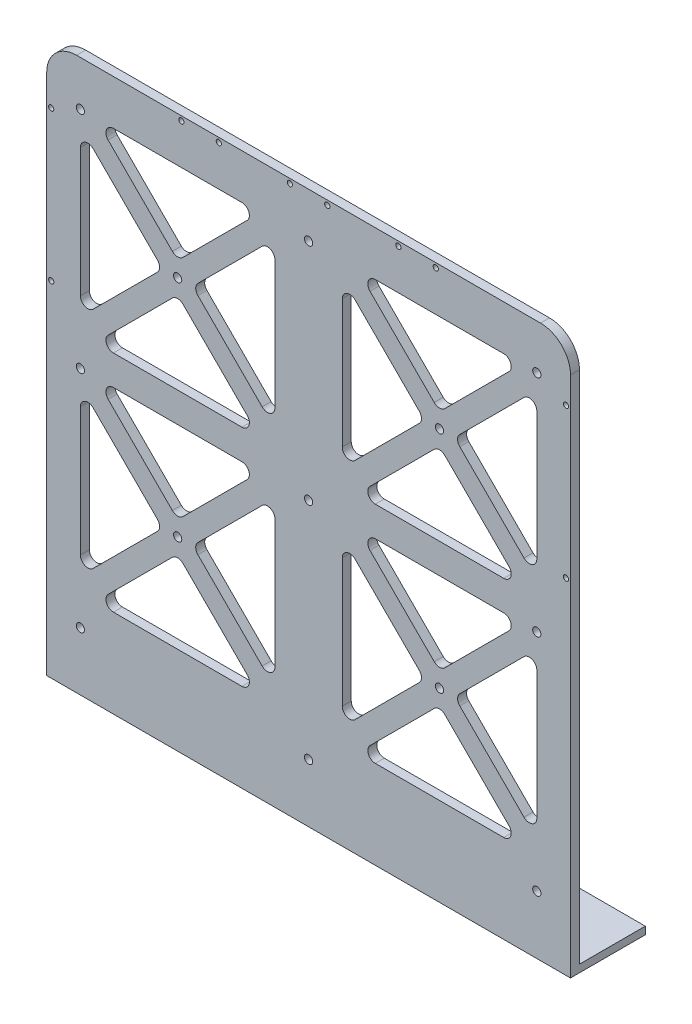
SolidWorks part; units mm, degrees
material "6061 合金"
ref_plane "前视基准面" through (0, 0, 0) normal (0, 0, 1) x (1, 0, 0)
ref_plane "上视基准面" through (0, 0, 0) normal (0, 1, 0) x (1, 0, 0)
ref_plane "右视基准面" through (0, 0, 0) normal (1, 0, 0) x (0, 0, -1)
other "Configuration Table"
sketch "草图1" plane through (0, 0, 0) normal (0, 1, 0) x (1, 0, 0)
  line L0 (0, 55.3951) -> (0, -55.5471) construction
  line L1 (-216.8213, 25) -> (288.5349, 25) construction
  line L2 (-175, 50) -> (175, 50)
  line L3 (-175, 50) -> (-175, 0)
  line L4 (-175, 0) -> (175, 0)
  line L5 (175, 50) -> (175, 0)
  circle A0 centre (130, 25) radius 2.75
  circle A1 centre (50, 25) radius 2.75
  circle A2 centre (-130, 25) radius 2.75
  circle A3 centre (-50, 25) radius 2.75
  dimension "D3" = 5.5
  dimension "D1" = 50
  dimension "D2" = 350
  dimension "D4" = 80
  dimension "D5" = 50
extrude "凸台-拉伸1" add sketch "草图1" along normal blind 5
sketch "草图2" plane through (0, 5, 0) normal (0, 1, 0) x (1, 0, 0)
  line L0 (-175, 50) -> (-175, 0) construction
  line L1 (-175, 6) -> (175, 6)
  line L2 (-175, 6) -> (-175, 0)
  line L3 (-175, 0) -> (175, 0)
  line L4 (175, 6) -> (175, 0)
  dimension "D1" = 6
extrude "凸台-拉伸2" add sketch "草图2" along normal blind 364
sketch "草图3" plane through (0, 0, -6) normal (0, 0, -1) x (-1, 0, 0)
  line L0 (83.9645, 137.5355) -> (41.0355, 180.4645)
  line L1 (0, 0) -> (0, 572.5398) construction
  line L2 (44.5711, 189) -> (130.4289, 189)
  line L15 (133.9645, 180.4645) -> (91.0355, 137.5355)
  line L28 (44.5711, 339) -> (130.4289, 339)
  line L29 (133.9645, 330.4645) -> (91.0355, 287.5355)
  line L30 (83.9645, 287.5355) -> (41.0355, 330.4645)
  line L31 (-175, 369) -> (175, 369) construction
  line L32 (87.5, 645.5729) -> (87.5, -148.8574) construction
  line L33 (73.9645, 120.4645) -> (31.0355, 77.5355)
  line L34 (175, 369) -> (175, 5) construction
  line L35 (101.0355, 277.5355) -> (143.9645, 320.4645)
  line L36 (152.5, 316.9289) -> (152.5, 231.0711)
  line L37 (143.9645, 227.5355) -> (101.0355, 270.4645)
  line L38 (91.0355, 260.4645) -> (133.9645, 217.5355)
  line L39 (130.4289, 209) -> (44.5711, 209)
  line L40 (41.0355, 217.5355) -> (83.9645, 260.4645)
  line L41 (73.9645, 270.4645) -> (31.0355, 227.5355)
  line L42 (22.5, 231.0711) -> (22.5, 316.9289)
  line L43 (31.0355, 320.4645) -> (73.9645, 277.5355)
  line L104 (22.5, 81.0711) -> (22.5, 166.9289)
  line L105 (31.0355, 170.4645) -> (73.9645, 127.5355)
  line L106 (101.0355, 127.5355) -> (143.9645, 170.4645)
  line L107 (152.5, 166.9289) -> (152.5, 81.0711)
  line L108 (143.9645, 77.5355) -> (101.0355, 120.4645)
  line L109 (91.0355, 110.4645) -> (133.9645, 67.5355)
  line L110 (130.4289, 59) -> (44.5711, 59)
  line L111 (41.0355, 67.5355) -> (83.9645, 110.4645)
  line L124 (-91.0355, 137.5355) -> (-133.9645, 180.4645)
  line L125 (-130.4289, 189) -> (-44.5711, 189)
  line L126 (-41.0355, 180.4645) -> (-83.9645, 137.5355)
  line L127 (-101.0355, 120.4645) -> (-143.9645, 77.5355)
  line L128 (-152.5, 81.0711) -> (-152.5, 166.9289)
  line L129 (-143.9645, 170.4645) -> (-101.0355, 127.5355)
  line L130 (-73.9645, 127.5355) -> (-31.0355, 170.4645)
  line L131 (-22.5, 166.9289) -> (-22.5, 81.0711)
  line L132 (-31.0355, 77.5355) -> (-73.9645, 120.4645)
  line L133 (-83.9645, 110.4645) -> (-41.0355, 67.5355)
  line L134 (-44.5711, 59) -> (-130.4289, 59)
  line L135 (-133.9645, 67.5355) -> (-91.0355, 110.4645)
  line L148 (-91.0355, 287.5355) -> (-133.9645, 330.4645)
  line L149 (-130.4289, 339) -> (-44.5711, 339)
  line L150 (-41.0355, 330.4645) -> (-83.9645, 287.5355)
  line L151 (-101.0355, 270.4645) -> (-143.9645, 227.5355)
  line L152 (-152.5, 231.0711) -> (-152.5, 316.9289)
  line L153 (-143.9645, 320.4645) -> (-101.0355, 277.5355)
  line L154 (-73.9645, 277.5355) -> (-31.0355, 320.4645)
  line L155 (-22.5, 316.9289) -> (-22.5, 231.0711)
  line L156 (-31.0355, 227.5355) -> (-73.9645, 270.4645)
  line L157 (-83.9645, 260.4645) -> (-41.0355, 217.5355)
  line L158 (-44.5711, 209) -> (-130.4289, 209)
  line L159 (-133.9645, 217.5355) -> (-91.0355, 260.4645)
  line L160 (83.9645, -12.4645) -> (41.0355, 30.4645) [skipped]
  line L161 (133.9645, 30.4645) -> (91.0355, -12.4645) [skipped]
  line L162 (73.9645, -29.5355) -> (31.0355, -72.4645) [skipped]
  line L163 (22.5, -68.9289) -> (22.5, 16.9289) [skipped]
  line L164 (31.0355, 20.4645) -> (73.9645, -22.4645) [skipped]
  line L165 (101.0355, -22.4645) -> (143.9645, 20.4645) [skipped]
  line L166 (152.5, 16.9289) -> (152.5, -68.9289) [skipped]
  line L167 (143.9645, -72.4645) -> (101.0355, -29.5355) [skipped]
  line L168 (91.0355, -39.5355) -> (133.9645, -82.4645) [skipped]
  line L169 (130.4289, -91) -> (44.5711, -91) [skipped]
  line L170 (41.0355, -82.4645) -> (83.9645, -39.5355) [skipped]
  line L171 (-91.0355, -12.4645) -> (-133.9645, 30.4645) [skipped]
  line L172 (-41.0355, 30.4645) -> (-83.9645, -12.4645) [skipped]
  line L173 (-101.0355, -29.5355) -> (-143.9645, -72.4645) [skipped]
  line L174 (-152.5, -68.9289) -> (-152.5, 16.9289) [skipped]
  line L175 (-143.9645, 20.4645) -> (-101.0355, -22.4645) [skipped]
  line L176 (-73.9645, -22.4645) -> (-31.0355, 20.4645) [skipped]
  line L177 (-22.5, 16.9289) -> (-22.5, -68.9289) [skipped]
  line L178 (-31.0355, -72.4645) -> (-73.9645, -29.5355) [skipped]
  line L179 (-83.9645, -39.5355) -> (-41.0355, -82.4645) [skipped]
  line L180 (-44.5711, -91) -> (-130.4289, -91) [skipped]
  line L181 (-133.9645, -82.4645) -> (-91.0355, -39.5355) [skipped]
  line L182 (44.5711, 39) -> (130.4289, 39) [skipped]
  line L183 (-130.4289, 39) -> (-44.5711, 39) [skipped]
  arc A0 (22.5, 316.9289) -> (31.0355, 320.4645) centre (27.5, 316.9289) cw
  arc A1 (31.0355, 227.5355) -> (22.5, 231.0711) centre (27.5, 231.0711) cw
  arc A2 (73.9645, 270.4645) -> (73.9645, 277.5355) centre (70.4289, 274) ccw
  arc A3 (44.5711, 209) -> (41.0355, 217.5355) centre (44.5711, 214) cw
  arc A4 (130.4289, 209) -> (133.9645, 217.5355) centre (130.4289, 214) ccw
  arc A5 (91.0355, 260.4645) -> (83.9645, 260.4645) centre (87.5, 256.9289) ccw
  arc A6 (101.0355, 270.4645) -> (101.0355, 277.5355) centre (104.5711, 274) cw
  arc A7 (143.9645, 227.5355) -> (152.5, 231.0711) centre (147.5, 231.0711) ccw
  arc A8 (152.5, 316.9289) -> (143.9645, 320.4645) centre (147.5, 316.9289) ccw
  arc A9 (91.0355, 287.5355) -> (83.9645, 287.5355) centre (87.5, 291.0711) cw
  arc A10 (133.9645, 330.4645) -> (130.4289, 339) centre (130.4289, 334) ccw
  arc A11 (41.0355, 330.4645) -> (44.5711, 339) centre (44.5711, 334) cw
  arc A12 (41.0355, 180.4645) -> (44.5711, 189) centre (44.5711, 184) cw
  arc A13 (91.0355, 137.5355) -> (83.9645, 137.5355) centre (87.5, 141.0711) cw
  arc A14 (133.9645, 180.4645) -> (130.4289, 189) centre (130.4289, 184) ccw
  arc A15 (73.9645, 120.4645) -> (73.9645, 127.5355) centre (70.4289, 124) ccw
  arc A16 (31.0355, 77.5355) -> (22.5, 81.0711) centre (27.5, 81.0711) cw
  arc A17 (22.5, 166.9289) -> (31.0355, 170.4645) centre (27.5, 166.9289) cw
  arc A18 (152.5, 166.9289) -> (143.9645, 170.4645) centre (147.5, 166.9289) ccw
  arc A19 (101.0355, 120.4645) -> (101.0355, 127.5355) centre (104.5711, 124) cw
  arc A20 (143.9645, 77.5355) -> (152.5, 81.0711) centre (147.5, 81.0711) ccw
  arc A21 (91.0355, 110.4645) -> (83.9645, 110.4645) centre (87.5, 106.9289) ccw
  arc A22 (130.4289, 59) -> (133.9645, 67.5355) centre (130.4289, 64) ccw
  arc A23 (44.5711, 59) -> (41.0355, 67.5355) centre (44.5711, 64) cw
  arc A36 (-133.9645, 180.4645) -> (-130.4289, 189) centre (-130.4289, 184) cw
  arc A37 (-83.9645, 137.5355) -> (-91.0355, 137.5355) centre (-87.5, 141.0711) cw
  arc A38 (-41.0355, 180.4645) -> (-44.5711, 189) centre (-44.5711, 184) ccw
  arc A39 (-101.0355, 120.4645) -> (-101.0355, 127.5355) centre (-104.5711, 124) ccw
  arc A40 (-143.9645, 77.5355) -> (-152.5, 81.0711) centre (-147.5, 81.0711) cw
  arc A41 (-152.5, 166.9289) -> (-143.9645, 170.4645) centre (-147.5, 166.9289) cw
  arc A42 (-22.5, 166.9289) -> (-31.0355, 170.4645) centre (-27.5, 166.9289) ccw
  arc A43 (-73.9645, 120.4645) -> (-73.9645, 127.5355) centre (-70.4289, 124) cw
  arc A44 (-31.0355, 77.5355) -> (-22.5, 81.0711) centre (-27.5, 81.0711) ccw
  arc A45 (-83.9645, 110.4645) -> (-91.0355, 110.4645) centre (-87.5, 106.9289) ccw
  arc A46 (-44.5711, 59) -> (-41.0355, 67.5355) centre (-44.5711, 64) ccw
  arc A47 (-130.4289, 59) -> (-133.9645, 67.5355) centre (-130.4289, 64) cw
  arc A60 (-133.9645, 330.4645) -> (-130.4289, 339) centre (-130.4289, 334) cw
  arc A61 (-83.9645, 287.5355) -> (-91.0355, 287.5355) centre (-87.5, 291.0711) cw
  arc A62 (-41.0355, 330.4645) -> (-44.5711, 339) centre (-44.5711, 334) ccw
  arc A63 (-101.0355, 270.4645) -> (-101.0355, 277.5355) centre (-104.5711, 274) ccw
  arc A64 (-143.9645, 227.5355) -> (-152.5, 231.0711) centre (-147.5, 231.0711) cw
  arc A65 (-152.5, 316.9289) -> (-143.9645, 320.4645) centre (-147.5, 316.9289) cw
  arc A66 (-22.5, 316.9289) -> (-31.0355, 320.4645) centre (-27.5, 316.9289) ccw
  arc A67 (-73.9645, 270.4645) -> (-73.9645, 277.5355) centre (-70.4289, 274) cw
  arc A68 (-31.0355, 227.5355) -> (-22.5, 231.0711) centre (-27.5, 231.0711) ccw
  arc A69 (-83.9645, 260.4645) -> (-91.0355, 260.4645) centre (-87.5, 256.9289) ccw
  arc A70 (-44.5711, 209) -> (-41.0355, 217.5355) centre (-44.5711, 214) ccw
  arc A71 (-130.4289, 209) -> (-133.9645, 217.5355) centre (-130.4289, 214) cw
  circle A72 centre (87.5, 274) radius 2.75
  circle A73 centre (87.5, 124) radius 2.75
  circle A75 centre (-87.5, 124) radius 2.75
  circle A77 centre (-87.5, 274) radius 2.75
  circle A78 centre (152.5, 339) radius 2.75
  circle A79 centre (152.5, 189) radius 2.75
  circle A80 centre (152.5, 39) radius 2.75
  circle A81 centre (-152.5, 39) radius 2.75
  circle A82 centre (-152.5, 189) radius 2.75
  circle A83 centre (-152.5, 339) radius 2.75
  circle A84 centre (0, 339) radius 2.75
  circle A85 centre (0, 189) radius 2.75
  circle A86 centre (0, 39) radius 2.75
  arc A87 (91.0355, -12.4645) -> (83.9645, -12.4645) centre (87.5, -8.9289) cw [skipped]
  arc A88 (73.9645, -29.5355) -> (73.9645, -22.4645) centre (70.4289, -26) ccw [skipped]
  arc A89 (31.0355, -72.4645) -> (22.5, -68.9289) centre (27.5, -68.9289) cw [skipped]
  arc A90 (22.5, 16.9289) -> (31.0355, 20.4645) centre (27.5, 16.9289) cw [skipped]
  arc A91 (152.5, 16.9289) -> (143.9645, 20.4645) centre (147.5, 16.9289) ccw [skipped]
  arc A92 (101.0355, -29.5355) -> (101.0355, -22.4645) centre (104.5711, -26) cw [skipped]
  arc A93 (143.9645, -72.4645) -> (152.5, -68.9289) centre (147.5, -68.9289) ccw [skipped]
  arc A94 (91.0355, -39.5355) -> (83.9645, -39.5355) centre (87.5, -43.0711) ccw [skipped]
  arc A95 (130.4289, -91) -> (133.9645, -82.4645) centre (130.4289, -86) ccw [skipped]
  arc A96 (44.5711, -91) -> (41.0355, -82.4645) centre (44.5711, -86) cw [skipped]
  arc A97 (-83.9645, -12.4645) -> (-91.0355, -12.4645) centre (-87.5, -8.9289) cw [skipped]
  arc A98 (-101.0355, -29.5355) -> (-101.0355, -22.4645) centre (-104.5711, -26) ccw [skipped]
  arc A99 (-143.9645, -72.4645) -> (-152.5, -68.9289) centre (-147.5, -68.9289) cw [skipped]
  arc A100 (-152.5, 16.9289) -> (-143.9645, 20.4645) centre (-147.5, 16.9289) cw [skipped]
  arc A101 (-22.5, 16.9289) -> (-31.0355, 20.4645) centre (-27.5, 16.9289) ccw [skipped]
  arc A102 (-73.9645, -29.5355) -> (-73.9645, -22.4645) centre (-70.4289, -26) cw [skipped]
  arc A103 (-31.0355, -72.4645) -> (-22.5, -68.9289) centre (-27.5, -68.9289) ccw [skipped]
  arc A104 (-83.9645, -39.5355) -> (-91.0355, -39.5355) centre (-87.5, -43.0711) ccw [skipped]
  arc A105 (-44.5711, -91) -> (-41.0355, -82.4645) centre (-44.5711, -86) ccw [skipped]
  arc A106 (-130.4289, -91) -> (-133.9645, -82.4645) centre (-130.4289, -86) cw [skipped]
  circle A107 centre (87.5, -26) radius 2.75 [skipped]
  circle A108 centre (-87.5, -26) radius 2.75 [skipped]
  arc A109 (133.9645, 30.4645) -> (130.4289, 39) centre (130.4289, 34) ccw [skipped]
  arc A110 (41.0355, 30.4645) -> (44.5711, 39) centre (44.5711, 34) cw [skipped]
  arc A111 (-41.0355, 30.4645) -> (-44.5711, 39) centre (-44.5711, 34) ccw [skipped]
  arc A112 (-133.9645, 30.4645) -> (-130.4289, 39) centre (-130.4289, 34) cw [skipped]
  point P12 (87.5, 274)
  point P25 (87.5, 274)
  point P43 (87.5, 284)
  point P46 (142.5, 339)
  point P49 (32.5, 339)
  dimension "D7" = 5
  dimension "D12" = 5.5
  dimension "D17" = 5.5
  dimension "D20" = 5.5
  dimension "D1" = 45
  dimension "D2" = 45
  dimension "D3" = 110
  dimension "D4" = 30
  dimension "D5" = 10
  dimension "D6" = 4
  dimension "D8" = 3
  dimension "D9" = 2
  dimension "D10" = 20
  dimension "D11" = 45
  dimension "D15" = 150
  dimension "D16" = 175
  dimension "D18" = 3
  dimension "D19" = 150
  dimension "D13" = 3
  dimension "D14" = 2
  dimension "D21" = 3
extrude "切除-拉伸1" cut sketch "草图3" against normal blind 500
sketch "草图4" plane through (0, 0, 0) normal (0, 0, 1) x (1, 0, 0)
  line L0 (0, 0) -> (0, 524.5854) construction
  line L1 (-175, 0) -> (175, 0) construction
  line L2 (-175, 369) -> (175, 369) construction
  circle A0 centre (60, 366) radius 1.75
  circle A1 centre (85, 366) radius 1.75
  circle A2 centre (12.5, 366) radius 1.75
  circle A3 centre (-12.5, 366) radius 1.75
  circle A4 centre (-85, 366) radius 1.75
  circle A5 centre (-60, 366) radius 1.75
  dimension "D1" = 3.5
  dimension "D2" = 3
  dimension "D3" = 60
  dimension "D4" = 25
  dimension "D5" = 12.5
extrude "切除-拉伸2" cut sketch "草图4" against normal blind 10
fillet "圆角1" radius 20 2 edges at (-175, 369, -3) (175, 369, -3)
sketch "草图5" plane through (0, 0, -6) normal (0, 0, -1) x (-1, 0, 0)
  line L0 (0, 431.6761) -> (0, -91.3276) construction
  line L1 (172, 381.63) -> (172, -6.2467) construction
  line L2 (175, 349) -> (175, 5) construction
  line L3 (142.7928, 280) -> (227.4318, 280) construction
  line L4 (-175, 5) -> (175, 5) construction
  line L5 (164.8, 155.6) -> (170, 155.6)
  line L6 (164.8, 155.6) -> (164.8, 130.4)
  line L7 (164.8, 130.4) -> (170, 130.4)
  line L8 (170, 155.6) -> (170, 130.4)
  line L9 (164.8, 110.4) -> (170, 110.4)
  line L10 (164.8, 110.4) -> (164.8, 85.2)
  line L11 (164.8, 85.2) -> (170, 85.2)
  line L12 (170, 110.4) -> (170, 85.2)
  line L13 (164.8, 65.2) -> (170, 65.2)
  line L14 (164.8, 65.2) -> (164.8, 40)
  line L15 (164.8, 40) -> (170, 40)
  line L16 (170, 65.2) -> (170, 40)
  line L17 (-142.7928, 280) -> (-227.4318, 280) construction
  line L18 (-172, 381.63) -> (-172, -6.2467) construction
  line L19 (-170, 65.2) -> (-170, 40)
  line L20 (-164.8, 40) -> (-170, 40)
  line L21 (-164.8, 65.2) -> (-164.8, 40)
  line L22 (-164.8, 65.2) -> (-170, 65.2)
  line L23 (-170, 110.4) -> (-170, 85.2)
  line L24 (-164.8, 85.2) -> (-170, 85.2)
  line L25 (-164.8, 110.4) -> (-164.8, 85.2)
  line L26 (-164.8, 110.4) -> (-170, 110.4)
  line L27 (-170, 155.6) -> (-170, 130.4)
  line L28 (-164.8, 130.4) -> (-170, 130.4)
  line L29 (-164.8, 155.6) -> (-164.8, 130.4)
  line L30 (-164.8, 155.6) -> (-170, 155.6)
  circle A0 centre (172, 330) radius 1.75
  circle A1 centre (172, 230) radius 1.75
  circle A2 centre (-172, 230) radius 1.75
  circle A3 centre (-172, 330) radius 1.75
  point P48 (0, 0)
  dimension "D2" = 3.5
  dimension "D1" = 3
  dimension "D3" = 100
  dimension "D4" = 69
  dimension "D5" = 5.2
  dimension "D6" = 25.2
  dimension "D7" = 25.2
  dimension "D8" = 5.2
  dimension "D9" = 25.2
  dimension "D10" = 20
  dimension "D11" = 20
  dimension "D12" = 35
  dimension "D13" = 5
extrude "切除-拉伸3" cut sketch "草图5" against normal blind 10 contours A0 | A1 | A2 | A3
sketch "草图6" plane through (0, 0, -6) normal (0, 0, -1) x (-1, 0, 0)
  line L0 (170, 130.4) -> (170, 155.6) construction
  line L1 (170, 85.2) -> (170, 110.4) construction
  line L2 (170, 40) -> (170, 65.2) construction
  line L3 (167.4, 194.4171) -> (167.4, -43.5745) construction
  line L4 (164.8, 65.2) -> (164.8, 40) construction
  line L5 (170, 155.6) -> (164.8, 155.6) construction
  line L6 (164.8, 130.4) -> (170, 130.4) construction
  line L7 (170, 110.4) -> (164.8, 110.4) construction
  line L8 (164.8, 85.2) -> (170, 85.2) construction
  line L9 (170, 65.2) -> (164.8, 65.2) construction
  line L10 (164.8, 40) -> (170, 40) construction
  line L11 (0, 0) -> (0, 113.7492) construction
  line L12 (-175, 0) -> (175, 0) construction
  circle A0 centre (170, 154.05) radius 1.55
  circle A1 centre (170, 131.95) radius 1.55
  circle A2 centre (170, 108.85) radius 1.55
  circle A3 centre (170, 86.75) radius 1.55
  circle A4 centre (170, 63.65) radius 1.55
  circle A5 centre (170, 41.55) radius 1.55
  circle A6 centre (164.8, 41.55) radius 1.55
  circle A7 centre (164.8, 63.65) radius 1.55
  circle A8 centre (164.8, 86.75) radius 1.55
  circle A9 centre (164.8, 108.85) radius 1.55
  circle A10 centre (164.8, 131.95) radius 1.55
  circle A11 centre (164.8, 154.05) radius 1.55
  circle A12 centre (-164.8, 154.05) radius 1.55
  circle A13 centre (-164.8, 131.95) radius 1.55
  circle A14 centre (-164.8, 108.85) radius 1.55
  circle A15 centre (-164.8, 86.75) radius 1.55
  circle A16 centre (-164.8, 63.65) radius 1.55
  circle A17 centre (-164.8, 41.55) radius 1.55
  circle A18 centre (-170, 41.55) radius 1.55
  circle A19 centre (-170, 63.65) radius 1.55
  circle A20 centre (-170, 86.75) radius 1.55
  circle A21 centre (-170, 108.85) radius 1.55
  circle A22 centre (-170, 131.95) radius 1.55
  circle A23 centre (-170, 154.05) radius 1.55
  dimension "D1" = 3.1
extrude "切除-拉伸4" [suppressed] cut sketch "草图6" against normal blind 10
